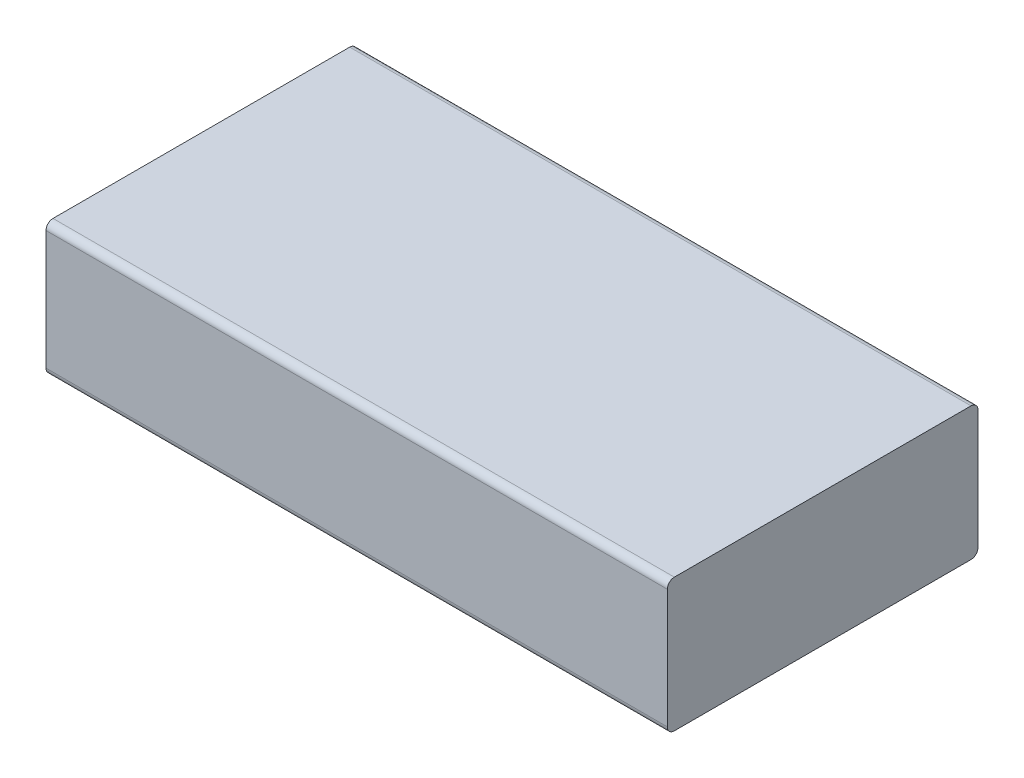
SolidWorks part; units mm, degrees
ref_plane "Front Plane" through (0, 0, 0) normal (0, 0, 1) x (1, 0, 0)
ref_plane "Top Plane" through (0, 0, 0) normal (0, 1, 0) x (1, 0, 0)
ref_plane "Right Plane" through (0, 0, 0) normal (1, 0, 0) x (0, 0, -1)
sketch "Sketch1" plane through (0, 0, 0) normal (1, 0, 0) x (0, 0, -1)
  line L1 (-44.45, -19.05) -> (44.45, -19.05)
  line L2 (-44.45, -19.05) -> (-44.45, 19.05)
  line L3 (-44.45, 19.05) -> (44.45, 19.05)
  line L4 (44.45, -19.05) -> (44.45, 19.05)
  line L5 (-44.45, -19.05) -> (44.45, 19.05) construction
  line L6 (-44.45, 19.05) -> (44.45, -19.05) construction
  point P0 (0, 0)
  dimension "D1" = 38.1
  dimension "D2" = 88.9
extrude "Boss-Extrude1" add sketch "Sketch1" along normal blind 177.8
fillet "Fillet1" radius 2 4 edges at (88.9, 19.05, 44.45) (88.9, 19.05, -44.45) (88.9, -19.05, -44.45) (88.9, -19.05, 44.45)
other "2x4<1>"
